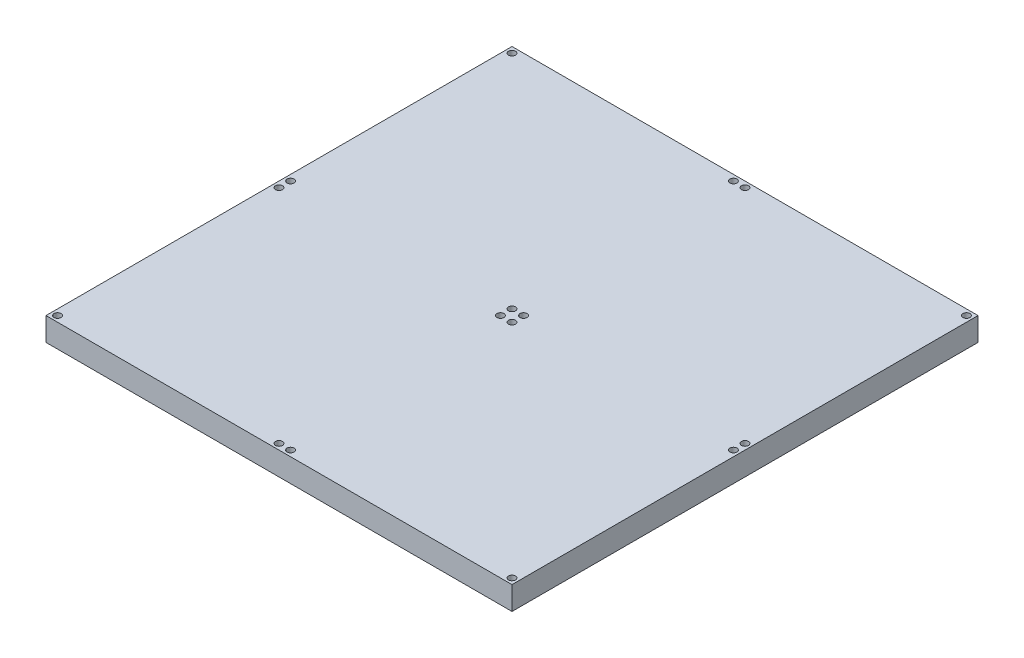
SolidWorks part; units mm, degrees
ref_plane "Front Plane" through (0, 0, 0) normal (0, 0, 1) x (1, 0, 0)
ref_plane "Top Plane" through (0, 0, 0) normal (0, 1, 0) x (1, 0, 0)
ref_plane "Right Plane" through (0, 0, 0) normal (1, 0, 0) x (0, 0, -1)
sketch "Sketch1" plane through (0, 0, 0) normal (0, 1, 0) x (1, 0, 0)
  line L1 (-25.4, -25.4) -> (25.4, -25.4)
  line L2 (-25.4, -25.4) -> (-25.4, 25.4)
  line L3 (-25.4, 25.4) -> (25.4, 25.4)
  line L4 (25.4, -25.4) -> (25.4, 25.4)
  line L5 (-25.4, -25.4) -> (25.4, 25.4) construction
  line L6 (-25.4, 25.4) -> (25.4, -25.4) construction
  point P0 (0, 0)
  dimension "D1" = 50.8
  dimension "D2" = 50.8
extrude "Boss-Extrude1" add sketch "Sketch1" along normal blind 5.08
sketch "Sketch11" plane through (0, 5.08, 0) normal (0, 1, 0) x (1, 0, 0)
  line L5 (-22.86, -22.86) -> (22.86, 22.86) construction
  line L6 (-22.86, 22.86) -> (22.86, -22.86) construction
  line L8 (-25.4, 25.4) -> (-22.86, 22.86) construction
  line L9 (0, -2.794) -> (0, 2.794) construction
  line L10 (-2.794, 0) -> (2.794, 0) construction
  circle A0 centre (-24.1428, 24.1428) radius 0.762
  circle A1 centre (24.1428, 24.1428) radius 0.762
  circle A2 centre (24.1428, -24.1428) radius 0.762
  circle A3 centre (-24.1428, -24.1428) radius 0.762
  point P0 (0, 0)
  dimension "D1" = 1.524
  dimension "D3" = 1.778
extrude "Cut-Extrude6" cut sketch "Sketch11" against normal blind 2.54
pattern_linear "LPattern1" count 2 spacing 50.8 along (0, 0, 1) count 2 spacing 50.8 along (1, 0, 0) of "Boss-Extrude1", "Cut-Extrude6"
